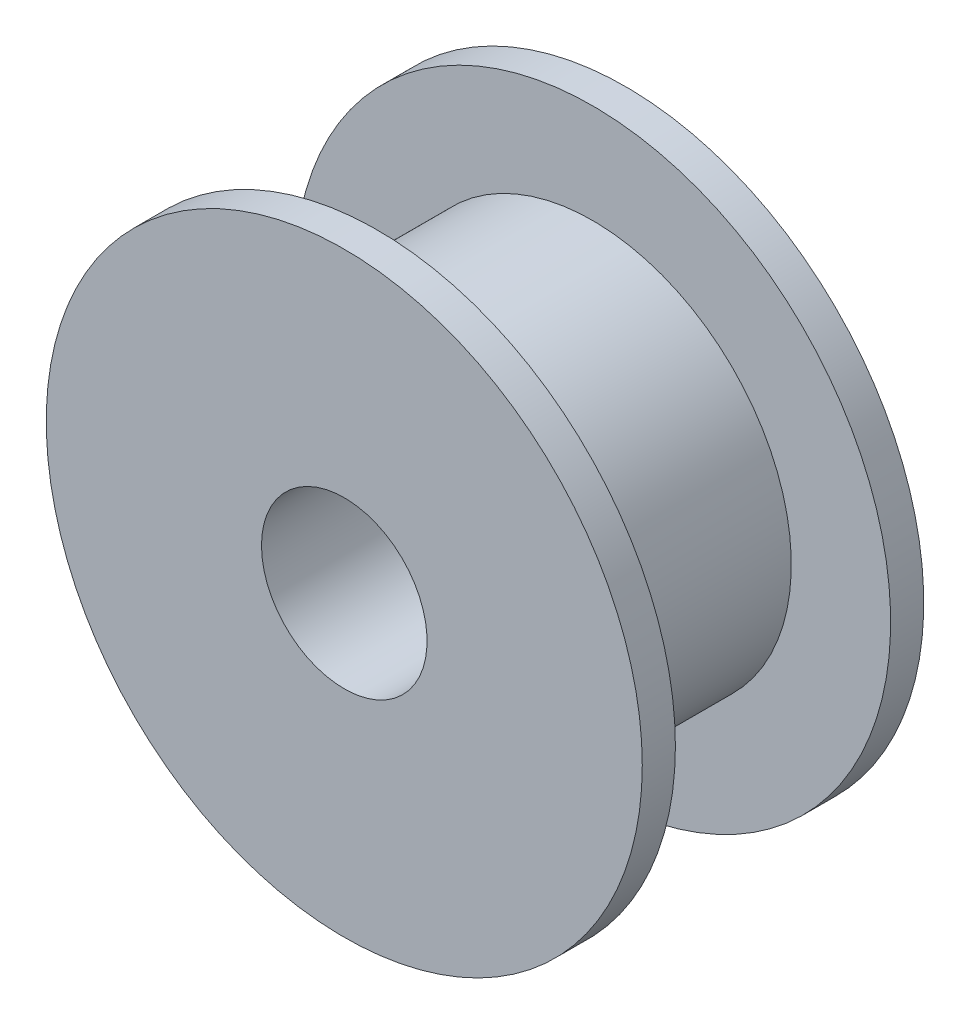
SolidWorks part; units mm, degrees
material "不锈钢 (铁素体)"
ref_plane "前视基准面" through (0, 0, 0) normal (0, 0, 1) x (1, 0, 0)
ref_plane "上视基准面" through (0, 0, 0) normal (0, 1, 0) x (1, 0, 0)
ref_plane "右视基准面" through (0, 0, 0) normal (1, 0, 0) x (0, 0, -1)
sketch "草图1" plane through (0, 0, 0) normal (0, 0, 1) x (1, 0, 0)
  circle A0 centre (0, 0) radius 2.5
  circle A1 centre (0, 0) radius 6
  dimension "D1" = 5
  dimension "D2" = 12
extrude "凸台-拉伸1" add sketch "草图1" along normal blind 6.5
sketch "草图2" plane through (0, 0, 6.5) normal (0, 0, 1) x (1, 0, 0)
  circle A0 centre (0, 0) radius 9
  circle A1 centre (0, 0) radius 2.5
  dimension "D1" = 18
  dimension "D2" = 5
extrude "凸台-拉伸3" add sketch "草图2" along normal blind 1
sketch "草图3" plane through (0, 0, 0) normal (0, 0, -1) x (-1, 0, 0)
  circle A0 centre (0, 0) radius 2.5
  circle A1 centre (0, 0) radius 9
  dimension "D1" = 18
  dimension "D2" = 5
extrude "凸台-拉伸4" add sketch "草图3" along normal blind 1
